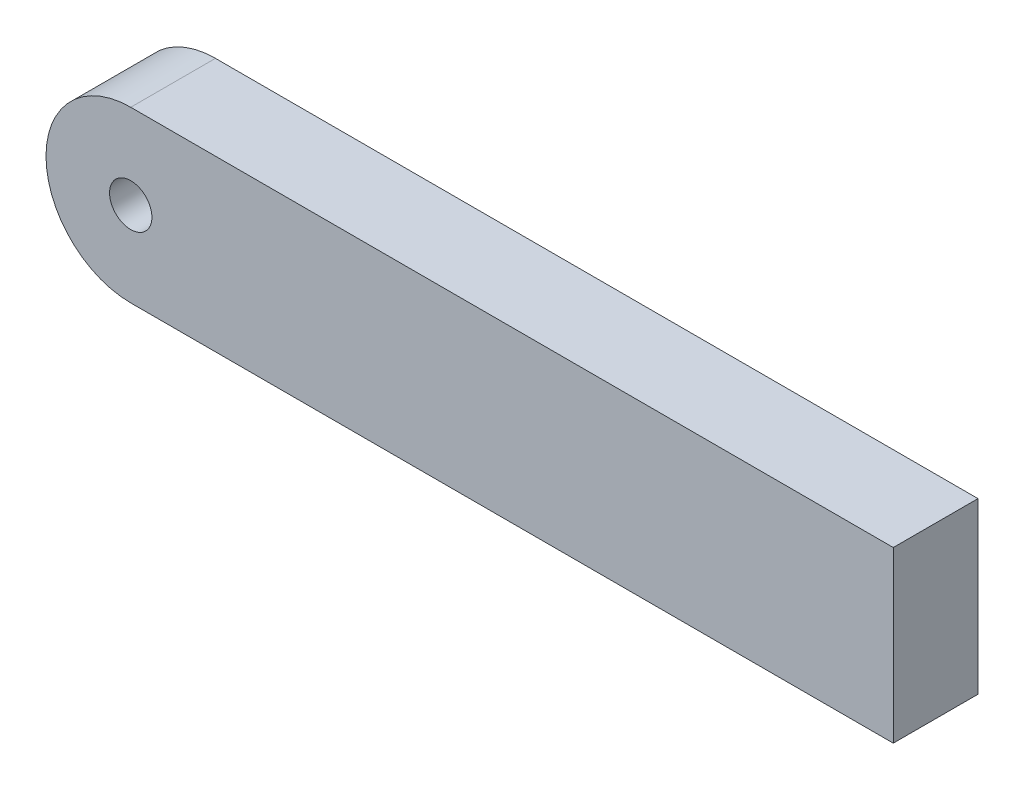
SolidWorks part; units mm, degrees
ref_plane "Front Plane" through (0, 0, 0) normal (0, 0, 1) x (1, 0, 0)
ref_plane "Top Plane" through (0, 0, 0) normal (0, 1, 0) x (1, 0, 0)
ref_plane "Right Plane" through (0, 0, 0) normal (1, 0, 0) x (0, 0, -1)
sketch "Sketch1" plane through (0, 0, 0) normal (0, 0, 1) x (1, 0, 0)
  line L0 (0, 10) -> (180, 10)
  line L1 (180, -10) -> (0, -10)
  line L2 (90, 10) -> (90, -10)
  circle A0 centre (0, 0) radius 2.5
  circle A1 centre (180, 0) radius 2.5
  arc A2 (0, -10) -> (0, 10) centre (0, 0) cw
  arc A3 (180, -10) -> (180, 10) centre (180, 0) ccw
  point P9 (-10, 0)
  dimension "D2" = 5
  dimension "D3" = 10
  dimension "D1" = 180
extrude "Boss-Extrude1" add sketch "Sketch1" along normal blind 10 contours A2 L1 L2 L0 A0
